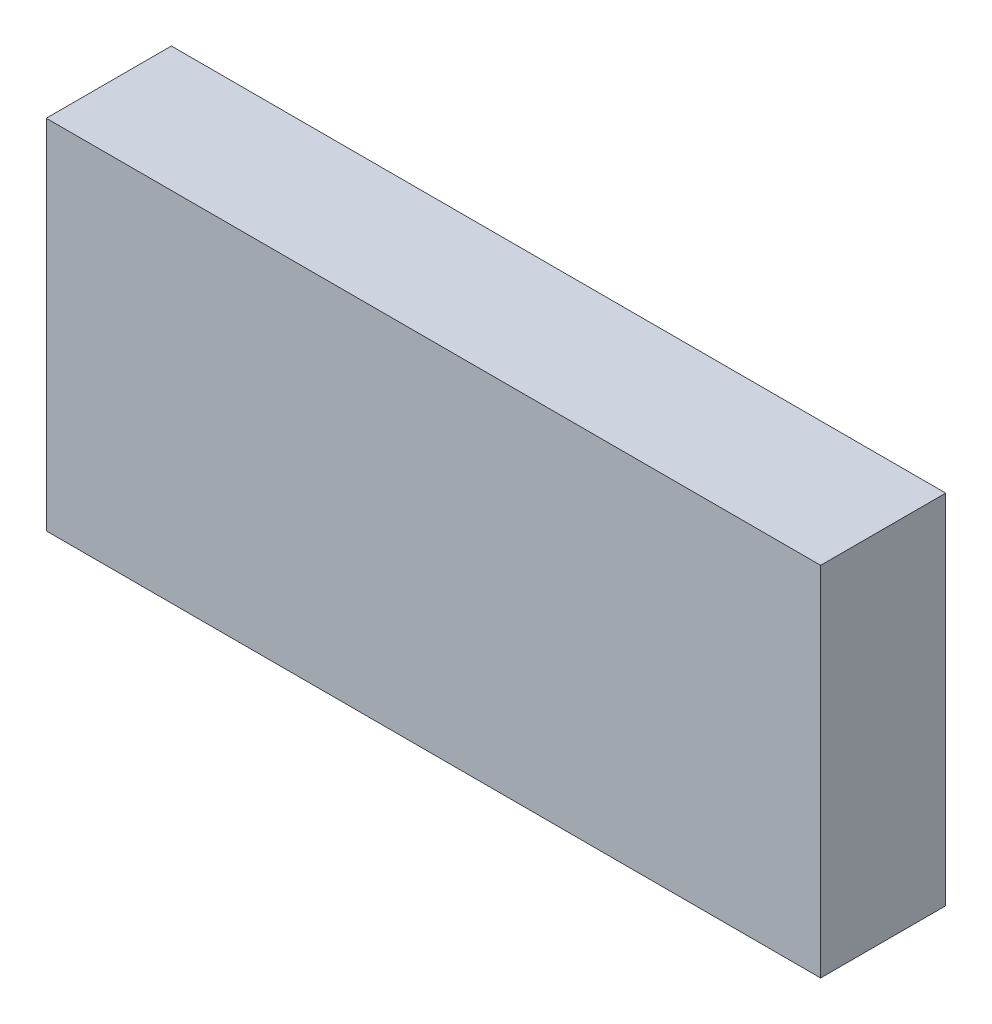
SolidWorks part; units mm, degrees
material "Cedar"
ref_plane "Front Plane" through (0, 0, 0) normal (0, 0, 1) x (1, 0, 0)
ref_plane "Top Plane" through (0, 0, 0) normal (0, 1, 0) x (1, 0, 0)
ref_plane "Right Plane" through (0, 0, 0) normal (1, 0, 0) x (0, 0, -1)
sketch "Sketch1" plane through (0, 0, 0) normal (0, 0, 1) x (1, 0, 0)
  line L0 (-65, -30) -> (65, 30) construction
  line L1 (-65, -30) -> (65, -30)
  line L2 (-65, -30) -> (-65, 30)
  line L3 (-65, 30) -> (65, 30)
  line L4 (65, -30) -> (65, 30)
  line L5 (-65, 30) -> (65, -30) construction
  point P4 (0, 0)
  dimension "D1" = 130
  dimension "D2" = 60
extrude "Boss-Extrude1" add sketch "Sketch1" along normal blind 21
